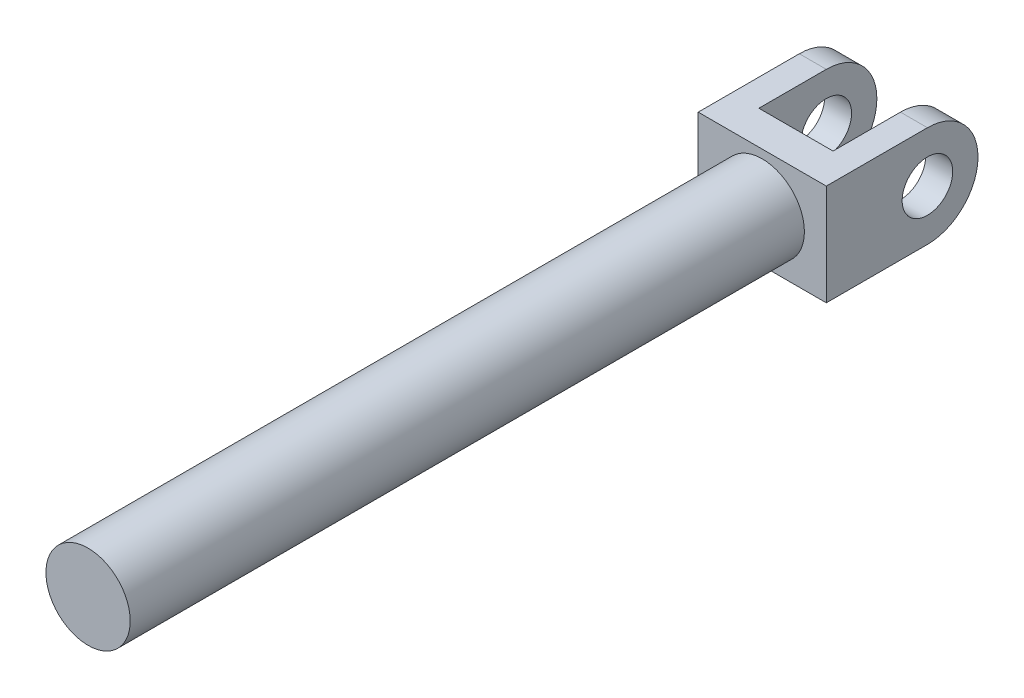
SolidWorks part; units mm, degrees
material "Q235"
ref_plane "前视基准面" through (0, 0, 0) normal (0, 0, 1) x (1, 0, 0)
ref_plane "上视基准面" through (0, 0, 0) normal (0, 1, 0) x (1, 0, 0)
ref_plane "右视基准面" through (0, 0, 0) normal (1, 0, 0) x (0, 0, -1)
sketch "草图1" plane through (0, 0, 0) normal (1, 0, 0) x (0, 0, -1)
  line L0 (0, -15) -> (-30, -15)
  line L1 (-30, -15) -> (-30, 15)
  line L2 (-30, 15) -> (0, 15)
  arc A0 (0, -15) -> (0, 15) centre (0, 0) ccw
  circle A1 centre (0, 0) radius 7.5
  dimension "D1" = 15
  dimension "D2" = 15
  dimension "D3" = 30
extrude "凸台-拉伸1" add sketch "草图1" along normal mid plane 38
sketch "草图2" plane through (0, 15, 0) normal (0, 1, 0) x (1, 0, 0)
  line L0 (19, 15) -> (-19, 15) construction
  line L1 (-11, 15) -> (11, 15)
  line L2 (-11, 15) -> (-11, -20)
  line L3 (-11, -20) -> (11, -20)
  line L4 (11, 15) -> (11, -20)
  line L5 (19, -30) -> (-19, -30) construction
  line L6 (0, -30) -> (0, 15) construction
  dimension "D1" = 22
  dimension "D2" = 10
extrude "切除-拉伸1" cut sketch "草图2" against normal through all
sketch "草图4" plane through (0, 0, 30) normal (0, 0, 1) x (1, 0, 0)
  circle A0 centre (0, 0) radius 12.5
  dimension "D1" = 25
extrude "凸台-拉伸2" add sketch "草图4" along normal blind 200
